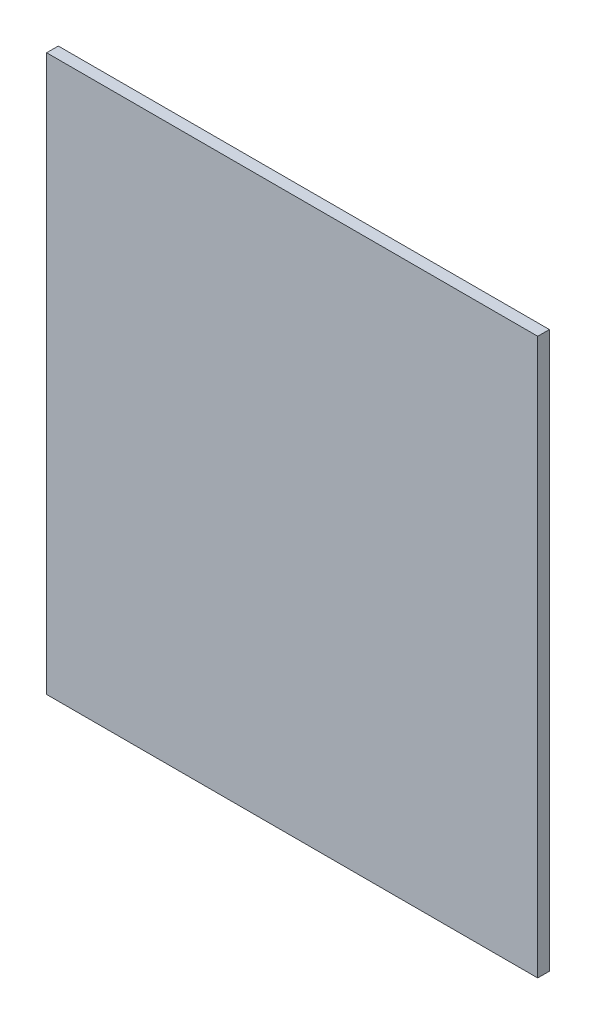
SolidWorks part; units mm, degrees
material "Pine"
ref_plane "Front Plane" through (0, 0, 0) normal (0, 0, 1) x (1, 0, 0)
ref_plane "Top Plane" through (0, 0, 0) normal (0, 1, 0) x (1, 0, 0)
ref_plane "Right Plane" through (0, 0, 0) normal (1, 0, 0) x (0, 0, -1)
sketch "Sketch1" plane through (0, 0, 0) normal (0, 0, 1) x (1, 0, 0)
  line L1 (0, 0) -> (534.6, 0)
  line L2 (0, 0) -> (0, 605)
  line L3 (0, 605) -> (534.6, 605)
  line L4 (534.6, 0) -> (534.6, 605)
  dimension "D1" = 605
  dimension "D2" = 534.6
extrude "Boss-Extrude1" add sketch "Sketch1" along normal blind 12.7
